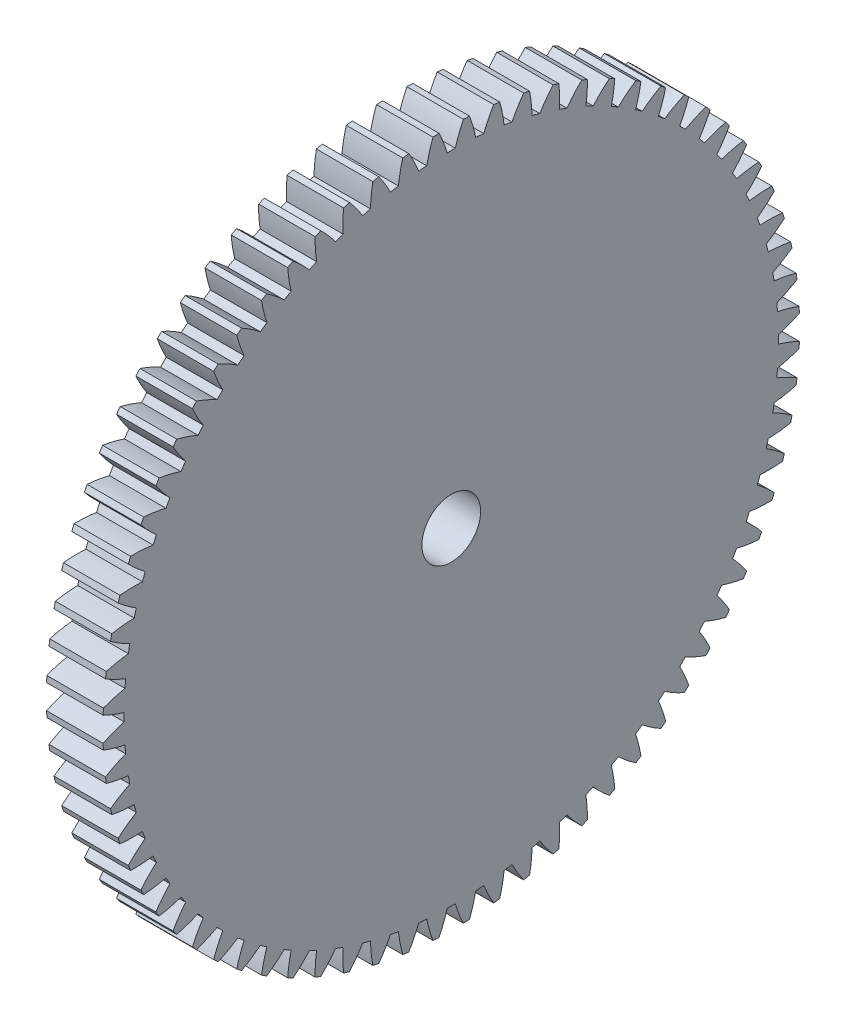
SolidWorks part; units mm, degrees
ref_plane "Front Plane" through (0, 0, 0) normal (0, 0, 1) x (1, 0, 0)
ref_plane "Top Plane" through (0, 0, 0) normal (0, 1, 0) x (1, 0, 0)
ref_plane "Right Plane" through (0, 0, 0) normal (1, 0, 0) x (0, 0, -1)
sketch "Sketch1" plane through (0, 0, 0) normal (0, 0, 1) x (1, 0, 0)
  line L0 (-10, 0) -> (60, 0) construction
  line L1 (0, 0) -> (0, 39.1583)
  line L2 (0, 0) -> (6.35, 0)
  line L3 (6.35, 0) -> (6.35, 39.1583)
  line L4 (6.35, 39.1583) -> (0, 39.1583)
  point P1 (0, 0)
  dimension "Diameter" = 78.3167
  dimension "Thickness" = 6.35
revolve "Revolve1" add sketch "Sketch1" angle 360 about L0
sketch "Sketch2" plane through (0, 0, 0) normal (-1, 0, 0) x (0, 0, 1)
  line L1 (0, 0) -> (0, 107) construction
  line L2 (0, 0) -> (-0.9058, 38.0892) construction
  line L3 (0, 0) -> (-3.3231, 76.1125) construction
  line L4 (-0.9058, 38.0892) -> (-1.6616, 38.0562) construction
  arc A0 (0.4536, 36.7764) -> (-0.4536, 36.7764) centre (0, 0) ccw
  arc A1 (1.3783, 39.1595) -> (-1.3783, 39.1595) centre (0, 0) ccw
  circle A2 centre (0, 0) radius 38.1 construction
  circle A3 centre (0, 0) radius 35.8023 construction
  arc A4 (-0.4536, 36.7764) -> (-1.3783, 39.1595) centre (-15.0738, 32.4744) ccw
  arc A5 (1.3783, 39.1595) -> (0.4536, 36.7764) centre (15.0738, 32.4744) ccw
  arc A6 (2.7534, 36.676) -> (2.0399, 39.1306) centre (-12.1861, 33.6646) ccw
  arc A7 (3.6571, 36.5969) -> (2.7534, 36.676) centre (0, 0) ccw
  arc A8 (4.786, 38.8903) -> (3.6571, 36.5969) centre (17.8467, 31.037) ccw
  arc A9 (4.786, 38.8903) -> (2.0399, 39.1306) centre (0, 0) ccw
  arc A10 (5.9395, 36.2965) -> (5.4426, 38.8039) centre (-9.2057, 34.5986) ccw
  arc A11 (6.8328, 36.1389) -> (5.9395, 36.2965) centre (0, 0) ccw
  arc A12 (8.1573, 38.3252) -> (6.8328, 36.1389) centre (20.4839, 29.3635) ccw
  arc A13 (8.1573, 38.3252) -> (5.4426, 38.8039) centre (0, 0) ccw
  arc A14 (9.0803, 35.6407) -> (8.8039, 38.1819) centre (-6.1552, 35.2692) ccw
  arc A15 (9.9566, 35.4059) -> (9.0803, 35.6407) centre (0, 0) ccw
  arc A16 (11.4665, 37.4684) -> (9.9566, 35.4059) centre (22.9651, 27.4665) ccw
  arc A17 (11.4665, 37.4684) -> (8.8039, 38.1819) centre (0, 0) ccw
  arc A18 (12.152, 34.7136) -> (12.0982, 37.2693) centre (-3.0578, 35.6715) ccw
  arc A19 (13.0045, 34.4034) -> (12.152, 34.7136) centre (0, 0) ccw
  arc A20 (14.6885, 36.3265) -> (13.0045, 34.4034) centre (25.2716, 25.3604) ccw
  arc A21 (14.6885, 36.3265) -> (12.0982, 37.2693) centre (0, 0) ccw
  arc A22 (15.1313, 33.5224) -> (15.3004, 36.073) centre (0.0628, 35.8022) ccw
  arc A23 (15.9535, 33.139) -> (15.1313, 33.5224) centre (0, 0) ccw
  arc A24 (17.7987, 34.9081) -> (15.9535, 33.139) centre (27.3857, 23.0613) ccw
  arc A25 (17.7987, 34.9081) -> (15.3004, 36.073) centre (0, 0) ccw
  arc A26 (17.9954, 32.0761) -> (18.3861, 34.6022) centre (3.1829, 35.6605) ccw
  arc A27 (18.781, 31.6225) -> (17.9954, 32.0761) centre (0, 0) ccw
  arc A28 (20.7734, 33.224) -> (18.781, 31.6225) centre (29.2915, 20.5867) ccw
  arc A29 (20.7734, 33.224) -> (18.3861, 34.6022) centre (0, 0) ccw
  arc A30 (20.7225, 30.3856) -> (21.3319, 32.8681) centre (6.2788, 35.2474) ccw
  arc A31 (21.4656, 29.8653) -> (20.7225, 30.3856) centre (0, 0) ccw
  arc A32 (23.59, 31.287) -> (21.4656, 29.8653) centre (30.9743, 17.9555) ccw
  arc A33 (23.59, 31.287) -> (21.3319, 32.8681) centre (0, 0) ccw
  arc A34 (23.292, 28.4639) -> (24.1154, 30.8838) centre (9.3269, 34.5661) ccw
  arc A35 (23.9869, 27.8808) -> (23.292, 28.4639) centre (0, 0) ccw
  arc A36 (26.227, 29.112) -> (23.9869, 27.8808) centre (32.4213, 15.1876) ccw
  arc A37 (26.227, 29.112) -> (24.1154, 30.8838) centre (0, 0) ccw
  arc A38 (25.6841, 26.3256) -> (26.7154, 28.6645) centre (12.3041, 33.6216) ccw
  arc A39 (26.3256, 25.6841) -> (25.6841, 26.3256) centre (0, 0) ccw
  arc A40 (28.6645, 26.7154) -> (26.3256, 25.6841) centre (33.6216, 12.3041) ccw
  arc A41 (28.6645, 26.7154) -> (26.7154, 28.6645) centre (0, 0) ccw
  arc A42 (27.8808, 23.9869) -> (29.112, 26.227) centre (15.1876, 32.4213) ccw
  arc A43 (28.4639, 23.292) -> (27.8808, 23.9869) centre (0, 0) ccw
  arc A44 (30.8838, 24.1154) -> (28.4639, 23.292) centre (34.5661, 9.3269) ccw
  arc A45 (30.8838, 24.1154) -> (29.112, 26.227) centre (0, 0) ccw
  arc A46 (29.8653, 21.4656) -> (31.287, 23.59) centre (17.9555, 30.9743) ccw
  arc A47 (30.3856, 20.7225) -> (29.8653, 21.4656) centre (0, 0) ccw
  arc A48 (32.8681, 21.3319) -> (30.3856, 20.7225) centre (35.2474, 6.2788) ccw
  arc A49 (32.8681, 21.3319) -> (31.287, 23.59) centre (0, 0) ccw
  arc A50 (31.6225, 18.781) -> (33.224, 20.7734) centre (20.5867, 29.2915) ccw
  arc A51 (32.0761, 17.9954) -> (31.6225, 18.781) centre (0, 0) ccw
  arc A52 (34.6022, 18.3861) -> (32.0761, 17.9954) centre (35.6605, 3.1829) ccw
  arc A53 (34.6022, 18.3861) -> (33.224, 20.7734) centre (0, 0) ccw
  arc A54 (33.139, 15.9535) -> (34.9081, 17.7987) centre (23.0613, 27.3857) ccw
  arc A55 (33.5224, 15.1313) -> (33.139, 15.9535) centre (0, 0) ccw
  arc A56 (36.073, 15.3004) -> (33.5224, 15.1313) centre (35.8022, 0.0628) ccw
  arc A57 (36.073, 15.3004) -> (34.9081, 17.7987) centre (0, 0) ccw
  arc A58 (34.4034, 13.0045) -> (36.3265, 14.6885) centre (25.3604, 25.2716) ccw
  arc A59 (34.7136, 12.152) -> (34.4034, 13.0045) centre (0, 0) ccw
  arc A60 (37.2693, 12.0982) -> (34.7136, 12.152) centre (35.6715, -3.0578) ccw
  arc A61 (37.2693, 12.0982) -> (36.3265, 14.6885) centre (0, 0) ccw
  arc A62 (35.4059, 9.9566) -> (37.4684, 11.4665) centre (27.4665, 22.9651) ccw
  arc A63 (35.6407, 9.0803) -> (35.4059, 9.9566) centre (0, 0) ccw
  arc A64 (38.1819, 8.8039) -> (35.6407, 9.0803) centre (35.2692, -6.1552) ccw
  arc A65 (38.1819, 8.8039) -> (37.4684, 11.4665) centre (0, 0) ccw
  arc A66 (36.1389, 6.8328) -> (38.3252, 8.1573) centre (29.3635, 20.4839) ccw
  arc A67 (36.2965, 5.9395) -> (36.1389, 6.8328) centre (0, 0) ccw
  arc A68 (38.8039, 5.4426) -> (36.2965, 5.9395) centre (34.5986, -9.2057) ccw
  arc A69 (38.8039, 5.4426) -> (38.3252, 8.1573) centre (0, 0) ccw
  arc A70 (36.5969, 3.6571) -> (38.8903, 4.786) centre (31.037, 17.8467) ccw
  arc A71 (36.676, 2.7534) -> (36.5969, 3.6571) centre (0, 0) ccw
  arc A72 (39.1306, 2.0399) -> (36.676, 2.7534) centre (33.6646, -12.1861) ccw
  arc A73 (39.1306, 2.0399) -> (38.8903, 4.786) centre (0, 0) ccw
  arc A74 (36.7764, 0.4536) -> (39.1595, 1.3783) centre (32.4744, 15.0738) ccw
  arc A75 (36.7764, -0.4536) -> (36.7764, 0.4536) centre (0, 0) ccw
  arc A76 (39.1595, -1.3783) -> (36.7764, -0.4536) centre (32.4744, -15.0738) ccw
  arc A77 (39.1595, -1.3783) -> (39.1595, 1.3783) centre (0, 0) ccw
  arc A78 (36.676, -2.7534) -> (39.1306, -2.0399) centre (33.6646, 12.1861) ccw
  arc A79 (36.5969, -3.6571) -> (36.676, -2.7534) centre (0, 0) ccw
  arc A80 (38.8903, -4.786) -> (36.5969, -3.6571) centre (31.037, -17.8467) ccw
  arc A81 (38.8903, -4.786) -> (39.1306, -2.0399) centre (0, 0) ccw
  arc A82 (36.2965, -5.9395) -> (38.8039, -5.4426) centre (34.5986, 9.2057) ccw
  arc A83 (36.1389, -6.8328) -> (36.2965, -5.9395) centre (0, 0) ccw
  arc A84 (38.3252, -8.1573) -> (36.1389, -6.8328) centre (29.3635, -20.4839) ccw
  arc A85 (38.3252, -8.1573) -> (38.8039, -5.4426) centre (0, 0) ccw
  arc A86 (35.6407, -9.0803) -> (38.1819, -8.8039) centre (35.2692, 6.1552) ccw
  arc A87 (35.4059, -9.9566) -> (35.6407, -9.0803) centre (0, 0) ccw
  arc A88 (37.4684, -11.4665) -> (35.4059, -9.9566) centre (27.4665, -22.9651) ccw
  arc A89 (37.4684, -11.4665) -> (38.1819, -8.8039) centre (0, 0) ccw
  arc A90 (34.7136, -12.152) -> (37.2693, -12.0982) centre (35.6715, 3.0578) ccw
  arc A91 (34.4034, -13.0045) -> (34.7136, -12.152) centre (0, 0) ccw
  arc A92 (36.3265, -14.6885) -> (34.4034, -13.0045) centre (25.3604, -25.2716) ccw
  arc A93 (36.3265, -14.6885) -> (37.2693, -12.0982) centre (0, 0) ccw
  arc A94 (33.5224, -15.1313) -> (36.073, -15.3004) centre (35.8022, -0.0628) ccw
  arc A95 (33.139, -15.9535) -> (33.5224, -15.1313) centre (0, 0) ccw
  arc A96 (34.9081, -17.7987) -> (33.139, -15.9535) centre (23.0613, -27.3857) ccw
  arc A97 (34.9081, -17.7987) -> (36.073, -15.3004) centre (0, 0) ccw
  arc A98 (32.0761, -17.9954) -> (34.6022, -18.3861) centre (35.6605, -3.1829) ccw
  arc A99 (31.6225, -18.781) -> (32.0761, -17.9954) centre (0, 0) ccw
  arc A100 (33.224, -20.7734) -> (31.6225, -18.781) centre (20.5867, -29.2915) ccw
  arc A101 (33.224, -20.7734) -> (34.6022, -18.3861) centre (0, 0) ccw
  arc A102 (30.3856, -20.7225) -> (32.8681, -21.3319) centre (35.2474, -6.2788) ccw
  arc A103 (29.8653, -21.4656) -> (30.3856, -20.7225) centre (0, 0) ccw
  arc A104 (31.287, -23.59) -> (29.8653, -21.4656) centre (17.9555, -30.9743) ccw
  arc A105 (31.287, -23.59) -> (32.8681, -21.3319) centre (0, 0) ccw
  arc A106 (28.4639, -23.292) -> (30.8838, -24.1154) centre (34.5661, -9.3269) ccw
  arc A107 (27.8808, -23.9869) -> (28.4639, -23.292) centre (0, 0) ccw
  arc A108 (29.112, -26.227) -> (27.8808, -23.9869) centre (15.1876, -32.4213) ccw
  arc A109 (29.112, -26.227) -> (30.8838, -24.1154) centre (0, 0) ccw
  arc A110 (26.3256, -25.6841) -> (28.6645, -26.7154) centre (33.6216, -12.3041) ccw
  arc A111 (25.6841, -26.3256) -> (26.3256, -25.6841) centre (0, 0) ccw
  arc A112 (26.7154, -28.6645) -> (25.6841, -26.3256) centre (12.3041, -33.6216) ccw
  arc A113 (26.7154, -28.6645) -> (28.6645, -26.7154) centre (0, 0) ccw
  arc A114 (23.9869, -27.8808) -> (26.227, -29.112) centre (32.4213, -15.1876) ccw
  arc A115 (23.292, -28.4639) -> (23.9869, -27.8808) centre (0, 0) ccw
  arc A116 (24.1154, -30.8838) -> (23.292, -28.4639) centre (9.3269, -34.5661) ccw
  arc A117 (24.1154, -30.8838) -> (26.227, -29.112) centre (0, 0) ccw
  arc A118 (21.4656, -29.8653) -> (23.59, -31.287) centre (30.9743, -17.9555) ccw
  arc A119 (20.7225, -30.3856) -> (21.4656, -29.8653) centre (0, 0) ccw
  arc A120 (21.3319, -32.8681) -> (20.7225, -30.3856) centre (6.2788, -35.2474) ccw
  arc A121 (21.3319, -32.8681) -> (23.59, -31.287) centre (0, 0) ccw
  arc A122 (18.781, -31.6225) -> (20.7734, -33.224) centre (29.2915, -20.5867) ccw
  arc A123 (17.9954, -32.0761) -> (18.781, -31.6225) centre (0, 0) ccw
  arc A124 (18.3861, -34.6022) -> (17.9954, -32.0761) centre (3.1829, -35.6605) ccw
  arc A125 (18.3861, -34.6022) -> (20.7734, -33.224) centre (0, 0) ccw
  arc A126 (15.9535, -33.139) -> (17.7987, -34.9081) centre (27.3857, -23.0613) ccw
  arc A127 (15.1313, -33.5224) -> (15.9535, -33.139) centre (0, 0) ccw
  arc A128 (15.3004, -36.073) -> (15.1313, -33.5224) centre (0.0628, -35.8022) ccw
  arc A129 (15.3004, -36.073) -> (17.7987, -34.9081) centre (0, 0) ccw
  arc A130 (13.0045, -34.4034) -> (14.6885, -36.3265) centre (25.2716, -25.3604) ccw
  arc A131 (12.152, -34.7136) -> (13.0045, -34.4034) centre (0, 0) ccw
  arc A132 (12.0982, -37.2693) -> (12.152, -34.7136) centre (-3.0578, -35.6715) ccw
  arc A133 (12.0982, -37.2693) -> (14.6885, -36.3265) centre (0, 0) ccw
  arc A134 (9.9566, -35.4059) -> (11.4665, -37.4684) centre (22.9651, -27.4665) ccw
  arc A135 (9.0803, -35.6407) -> (9.9566, -35.4059) centre (0, 0) ccw
  arc A136 (8.8039, -38.1819) -> (9.0803, -35.6407) centre (-6.1552, -35.2692) ccw
  arc A137 (8.8039, -38.1819) -> (11.4665, -37.4684) centre (0, 0) ccw
  arc A138 (6.8328, -36.1389) -> (8.1573, -38.3252) centre (20.4839, -29.3635) ccw
  arc A139 (5.9395, -36.2965) -> (6.8328, -36.1389) centre (0, 0) ccw
  arc A140 (5.4426, -38.8039) -> (5.9395, -36.2965) centre (-9.2057, -34.5986) ccw
  arc A141 (5.4426, -38.8039) -> (8.1573, -38.3252) centre (0, 0) ccw
  arc A142 (3.6571, -36.5969) -> (4.786, -38.8903) centre (17.8467, -31.037) ccw
  arc A143 (2.7534, -36.676) -> (3.6571, -36.5969) centre (0, 0) ccw
  arc A144 (2.0399, -39.1306) -> (2.7534, -36.676) centre (-12.1861, -33.6646) ccw
  arc A145 (2.0399, -39.1306) -> (4.786, -38.8903) centre (0, 0) ccw
  arc A146 (0.4536, -36.7764) -> (1.3783, -39.1595) centre (15.0738, -32.4744) ccw
  arc A147 (-0.4536, -36.7764) -> (0.4536, -36.7764) centre (0, 0) ccw
  arc A148 (-1.3783, -39.1595) -> (-0.4536, -36.7764) centre (-15.0738, -32.4744) ccw
  arc A149 (-1.3783, -39.1595) -> (1.3783, -39.1595) centre (0, 0) ccw
  arc A150 (-2.7534, -36.676) -> (-2.0399, -39.1306) centre (12.1861, -33.6646) ccw
  arc A151 (-3.6571, -36.5969) -> (-2.7534, -36.676) centre (0, 0) ccw
  arc A152 (-4.786, -38.8903) -> (-3.6571, -36.5969) centre (-17.8467, -31.037) ccw
  arc A153 (-4.786, -38.8903) -> (-2.0399, -39.1306) centre (0, 0) ccw
  arc A154 (-5.9395, -36.2965) -> (-5.4426, -38.8039) centre (9.2057, -34.5986) ccw
  arc A155 (-6.8328, -36.1389) -> (-5.9395, -36.2965) centre (0, 0) ccw
  arc A156 (-8.1573, -38.3252) -> (-6.8328, -36.1389) centre (-20.4839, -29.3635) ccw
  arc A157 (-8.1573, -38.3252) -> (-5.4426, -38.8039) centre (0, 0) ccw
  arc A158 (-9.0803, -35.6407) -> (-8.8039, -38.1819) centre (6.1552, -35.2692) ccw
  arc A159 (-9.9566, -35.4059) -> (-9.0803, -35.6407) centre (0, 0) ccw
  arc A160 (-11.4665, -37.4684) -> (-9.9566, -35.4059) centre (-22.9651, -27.4665) ccw
  arc A161 (-11.4665, -37.4684) -> (-8.8039, -38.1819) centre (0, 0) ccw
  arc A162 (-12.152, -34.7136) -> (-12.0982, -37.2693) centre (3.0578, -35.6715) ccw
  arc A163 (-13.0045, -34.4034) -> (-12.152, -34.7136) centre (0, 0) ccw
  arc A164 (-14.6885, -36.3265) -> (-13.0045, -34.4034) centre (-25.2716, -25.3604) ccw
  arc A165 (-14.6885, -36.3265) -> (-12.0982, -37.2693) centre (0, 0) ccw
  arc A166 (-15.1313, -33.5224) -> (-15.3004, -36.073) centre (-0.0628, -35.8022) ccw
  arc A167 (-15.9535, -33.139) -> (-15.1313, -33.5224) centre (0, 0) ccw
  arc A168 (-17.7987, -34.9081) -> (-15.9535, -33.139) centre (-27.3857, -23.0613) ccw
  arc A169 (-17.7987, -34.9081) -> (-15.3004, -36.073) centre (0, 0) ccw
  arc A170 (-17.9954, -32.0761) -> (-18.3861, -34.6022) centre (-3.1829, -35.6605) ccw
  arc A171 (-18.781, -31.6225) -> (-17.9954, -32.0761) centre (0, 0) ccw
  arc A172 (-20.7734, -33.224) -> (-18.781, -31.6225) centre (-29.2915, -20.5867) ccw
  arc A173 (-20.7734, -33.224) -> (-18.3861, -34.6022) centre (0, 0) ccw
  arc A174 (-20.7225, -30.3856) -> (-21.3319, -32.8681) centre (-6.2788, -35.2474) ccw
  arc A175 (-21.4656, -29.8653) -> (-20.7225, -30.3856) centre (0, 0) ccw
  arc A176 (-23.59, -31.287) -> (-21.4656, -29.8653) centre (-30.9743, -17.9555) ccw
  arc A177 (-23.59, -31.287) -> (-21.3319, -32.8681) centre (0, 0) ccw
  arc A178 (-23.292, -28.4639) -> (-24.1154, -30.8838) centre (-9.3269, -34.5661) ccw
  arc A179 (-23.9869, -27.8808) -> (-23.292, -28.4639) centre (0, 0) ccw
  arc A180 (-26.227, -29.112) -> (-23.9869, -27.8808) centre (-32.4213, -15.1876) ccw
  arc A181 (-26.227, -29.112) -> (-24.1154, -30.8838) centre (0, 0) ccw
  arc A182 (-25.6841, -26.3256) -> (-26.7154, -28.6645) centre (-12.3041, -33.6216) ccw
  arc A183 (-26.3256, -25.6841) -> (-25.6841, -26.3256) centre (0, 0) ccw
  arc A184 (-28.6645, -26.7154) -> (-26.3256, -25.6841) centre (-33.6216, -12.3041) ccw
  arc A185 (-28.6645, -26.7154) -> (-26.7154, -28.6645) centre (0, 0) ccw
  arc A186 (-27.8808, -23.9869) -> (-29.112, -26.227) centre (-15.1876, -32.4213) ccw
  arc A187 (-28.4639, -23.292) -> (-27.8808, -23.9869) centre (0, 0) ccw
  arc A188 (-30.8838, -24.1154) -> (-28.4639, -23.292) centre (-34.5661, -9.3269) ccw
  arc A189 (-30.8838, -24.1154) -> (-29.112, -26.227) centre (0, 0) ccw
  arc A190 (-29.8653, -21.4656) -> (-31.287, -23.59) centre (-17.9555, -30.9743) ccw
  arc A191 (-30.3856, -20.7225) -> (-29.8653, -21.4656) centre (0, 0) ccw
  arc A192 (-32.8681, -21.3319) -> (-30.3856, -20.7225) centre (-35.2474, -6.2788) ccw
  arc A193 (-32.8681, -21.3319) -> (-31.287, -23.59) centre (0, 0) ccw
  arc A194 (-31.6225, -18.781) -> (-33.224, -20.7734) centre (-20.5867, -29.2915) ccw
  arc A195 (-32.0761, -17.9954) -> (-31.6225, -18.781) centre (0, 0) ccw
  arc A196 (-34.6022, -18.3861) -> (-32.0761, -17.9954) centre (-35.6605, -3.1829) ccw
  arc A197 (-34.6022, -18.3861) -> (-33.224, -20.7734) centre (0, 0) ccw
  arc A198 (-33.139, -15.9535) -> (-34.9081, -17.7987) centre (-23.0613, -27.3857) ccw
  arc A199 (-33.5224, -15.1313) -> (-33.139, -15.9535) centre (0, 0) ccw
  arc A200 (-36.073, -15.3004) -> (-33.5224, -15.1313) centre (-35.8022, -0.0628) ccw
  arc A201 (-36.073, -15.3004) -> (-34.9081, -17.7987) centre (0, 0) ccw
  arc A202 (-34.4034, -13.0045) -> (-36.3265, -14.6885) centre (-25.3604, -25.2716) ccw
  arc A203 (-34.7136, -12.152) -> (-34.4034, -13.0045) centre (0, 0) ccw
  arc A204 (-37.2693, -12.0982) -> (-34.7136, -12.152) centre (-35.6715, 3.0578) ccw
  arc A205 (-37.2693, -12.0982) -> (-36.3265, -14.6885) centre (0, 0) ccw
  arc A206 (-35.4059, -9.9566) -> (-37.4684, -11.4665) centre (-27.4665, -22.9651) ccw
  arc A207 (-35.6407, -9.0803) -> (-35.4059, -9.9566) centre (0, 0) ccw
  arc A208 (-38.1819, -8.8039) -> (-35.6407, -9.0803) centre (-35.2692, 6.1552) ccw
  arc A209 (-38.1819, -8.8039) -> (-37.4684, -11.4665) centre (0, 0) ccw
  arc A210 (-36.1389, -6.8328) -> (-38.3252, -8.1573) centre (-29.3635, -20.4839) ccw
  arc A211 (-36.2965, -5.9395) -> (-36.1389, -6.8328) centre (0, 0) ccw
  arc A212 (-38.8039, -5.4426) -> (-36.2965, -5.9395) centre (-34.5986, 9.2057) ccw
  arc A213 (-38.8039, -5.4426) -> (-38.3252, -8.1573) centre (0, 0) ccw
  arc A214 (-36.5969, -3.6571) -> (-38.8903, -4.786) centre (-31.037, -17.8467) ccw
  arc A215 (-36.676, -2.7534) -> (-36.5969, -3.6571) centre (0, 0) ccw
  arc A216 (-39.1306, -2.0399) -> (-36.676, -2.7534) centre (-33.6646, 12.1861) ccw
  arc A217 (-39.1306, -2.0399) -> (-38.8903, -4.786) centre (0, 0) ccw
  arc A218 (-36.7764, -0.4536) -> (-39.1595, -1.3783) centre (-32.4744, -15.0738) ccw
  arc A219 (-36.7764, 0.4536) -> (-36.7764, -0.4536) centre (0, 0) ccw
  arc A220 (-39.1595, 1.3783) -> (-36.7764, 0.4536) centre (-32.4744, 15.0738) ccw
  arc A221 (-39.1595, 1.3783) -> (-39.1595, -1.3783) centre (0, 0) ccw
  arc A222 (-36.676, 2.7534) -> (-39.1306, 2.0399) centre (-33.6646, -12.1861) ccw
  arc A223 (-36.5969, 3.6571) -> (-36.676, 2.7534) centre (0, 0) ccw
  arc A224 (-38.8903, 4.786) -> (-36.5969, 3.6571) centre (-31.037, 17.8467) ccw
  arc A225 (-38.8903, 4.786) -> (-39.1306, 2.0399) centre (0, 0) ccw
  arc A226 (-36.2965, 5.9395) -> (-38.8039, 5.4426) centre (-34.5986, -9.2057) ccw
  arc A227 (-36.1389, 6.8328) -> (-36.2965, 5.9395) centre (0, 0) ccw
  arc A228 (-38.3252, 8.1573) -> (-36.1389, 6.8328) centre (-29.3635, 20.4839) ccw
  arc A229 (-38.3252, 8.1573) -> (-38.8039, 5.4426) centre (0, 0) ccw
  arc A230 (-35.6407, 9.0803) -> (-38.1819, 8.8039) centre (-35.2692, -6.1552) ccw
  arc A231 (-35.4059, 9.9566) -> (-35.6407, 9.0803) centre (0, 0) ccw
  arc A232 (-37.4684, 11.4665) -> (-35.4059, 9.9566) centre (-27.4665, 22.9651) ccw
  arc A233 (-37.4684, 11.4665) -> (-38.1819, 8.8039) centre (0, 0) ccw
  arc A234 (-34.7136, 12.152) -> (-37.2693, 12.0982) centre (-35.6715, -3.0578) ccw
  arc A235 (-34.4034, 13.0045) -> (-34.7136, 12.152) centre (0, 0) ccw
  arc A236 (-36.3265, 14.6885) -> (-34.4034, 13.0045) centre (-25.3604, 25.2716) ccw
  arc A237 (-36.3265, 14.6885) -> (-37.2693, 12.0982) centre (0, 0) ccw
  arc A238 (-33.5224, 15.1313) -> (-36.073, 15.3004) centre (-35.8022, 0.0628) ccw
  arc A239 (-33.139, 15.9535) -> (-33.5224, 15.1313) centre (0, 0) ccw
  arc A240 (-34.9081, 17.7987) -> (-33.139, 15.9535) centre (-23.0613, 27.3857) ccw
  arc A241 (-34.9081, 17.7987) -> (-36.073, 15.3004) centre (0, 0) ccw
  arc A242 (-32.0761, 17.9954) -> (-34.6022, 18.3861) centre (-35.6605, 3.1829) ccw
  arc A243 (-31.6225, 18.781) -> (-32.0761, 17.9954) centre (0, 0) ccw
  arc A244 (-33.224, 20.7734) -> (-31.6225, 18.781) centre (-20.5867, 29.2915) ccw
  arc A245 (-33.224, 20.7734) -> (-34.6022, 18.3861) centre (0, 0) ccw
  arc A246 (-30.3856, 20.7225) -> (-32.8681, 21.3319) centre (-35.2474, 6.2788) ccw
  arc A247 (-29.8653, 21.4656) -> (-30.3856, 20.7225) centre (0, 0) ccw
  arc A248 (-31.287, 23.59) -> (-29.8653, 21.4656) centre (-17.9555, 30.9743) ccw
  arc A249 (-31.287, 23.59) -> (-32.8681, 21.3319) centre (0, 0) ccw
  arc A250 (-28.4639, 23.292) -> (-30.8838, 24.1154) centre (-34.5661, 9.3269) ccw
  arc A251 (-27.8808, 23.9869) -> (-28.4639, 23.292) centre (0, 0) ccw
  arc A252 (-29.112, 26.227) -> (-27.8808, 23.9869) centre (-15.1876, 32.4213) ccw
  arc A253 (-29.112, 26.227) -> (-30.8838, 24.1154) centre (0, 0) ccw
  arc A254 (-26.3256, 25.6841) -> (-28.6645, 26.7154) centre (-33.6216, 12.3041) ccw
  arc A255 (-25.6841, 26.3256) -> (-26.3256, 25.6841) centre (0, 0) ccw
  arc A256 (-26.7154, 28.6645) -> (-25.6841, 26.3256) centre (-12.3041, 33.6216) ccw
  arc A257 (-26.7154, 28.6645) -> (-28.6645, 26.7154) centre (0, 0) ccw
  arc A258 (-23.9869, 27.8808) -> (-26.227, 29.112) centre (-32.4213, 15.1876) ccw
  arc A259 (-23.292, 28.4639) -> (-23.9869, 27.8808) centre (0, 0) ccw
  arc A260 (-24.1154, 30.8838) -> (-23.292, 28.4639) centre (-9.3269, 34.5661) ccw
  arc A261 (-24.1154, 30.8838) -> (-26.227, 29.112) centre (0, 0) ccw
  arc A262 (-21.4656, 29.8653) -> (-23.59, 31.287) centre (-30.9743, 17.9555) ccw
  arc A263 (-20.7225, 30.3856) -> (-21.4656, 29.8653) centre (0, 0) ccw
  arc A264 (-21.3319, 32.8681) -> (-20.7225, 30.3856) centre (-6.2788, 35.2474) ccw
  arc A265 (-21.3319, 32.8681) -> (-23.59, 31.287) centre (0, 0) ccw
  arc A266 (-18.781, 31.6225) -> (-20.7734, 33.224) centre (-29.2915, 20.5867) ccw
  arc A267 (-17.9954, 32.0761) -> (-18.781, 31.6225) centre (0, 0) ccw
  arc A268 (-18.3861, 34.6022) -> (-17.9954, 32.0761) centre (-3.1829, 35.6605) ccw
  arc A269 (-18.3861, 34.6022) -> (-20.7734, 33.224) centre (0, 0) ccw
  arc A270 (-15.9535, 33.139) -> (-17.7987, 34.9081) centre (-27.3857, 23.0613) ccw
  arc A271 (-15.1313, 33.5224) -> (-15.9535, 33.139) centre (0, 0) ccw
  arc A272 (-15.3004, 36.073) -> (-15.1313, 33.5224) centre (-0.0628, 35.8022) ccw
  arc A273 (-15.3004, 36.073) -> (-17.7987, 34.9081) centre (0, 0) ccw
  arc A274 (-13.0045, 34.4034) -> (-14.6885, 36.3265) centre (-25.2716, 25.3604) ccw
  arc A275 (-12.152, 34.7136) -> (-13.0045, 34.4034) centre (0, 0) ccw
  arc A276 (-12.0982, 37.2693) -> (-12.152, 34.7136) centre (3.0578, 35.6715) ccw
  arc A277 (-12.0982, 37.2693) -> (-14.6885, 36.3265) centre (0, 0) ccw
  arc A278 (-9.9566, 35.4059) -> (-11.4665, 37.4684) centre (-22.9651, 27.4665) ccw
  arc A279 (-9.0803, 35.6407) -> (-9.9566, 35.4059) centre (0, 0) ccw
  arc A280 (-8.8039, 38.1819) -> (-9.0803, 35.6407) centre (6.1552, 35.2692) ccw
  arc A281 (-8.8039, 38.1819) -> (-11.4665, 37.4684) centre (0, 0) ccw
  arc A282 (-6.8328, 36.1389) -> (-8.1573, 38.3252) centre (-20.4839, 29.3635) ccw
  arc A283 (-5.9395, 36.2965) -> (-6.8328, 36.1389) centre (0, 0) ccw
  arc A284 (-5.4426, 38.8039) -> (-5.9395, 36.2965) centre (9.2057, 34.5986) ccw
  arc A285 (-5.4426, 38.8039) -> (-8.1573, 38.3252) centre (0, 0) ccw
  arc A286 (-3.6571, 36.5969) -> (-4.786, 38.8903) centre (-17.8467, 31.037) ccw
  arc A287 (-2.7534, 36.676) -> (-3.6571, 36.5969) centre (0, 0) ccw
  arc A288 (-2.0399, 39.1306) -> (-2.7534, 36.676) centre (12.1861, 33.6646) ccw
  arc A289 (-2.0399, 39.1306) -> (-4.786, 38.8903) centre (0, 0) ccw
  point P444 (0, 0)
  dimension "Root_dia" = 73.5584
  dimension "Overcut_dia" = 78.3675
  dimension "Pitch_dia" = 76.2
  dimension "Base_dia" = 71.6046
  dimension "Flank_rad" = 15.24
  dimension "Half_ang" = 2.5
  dimension "Half_CT" = 0.7565
extrude "Cut-Extrude1" cut sketch "Sketch2" against normal through all
sketch "Sketch5" plane through (0, 0, 0) normal (-1, 0, 0) x (0, 0, 1)
  circle A0 centre (0, 0) radius 3.302
  dimension "D1" = 6.604
extrude "Cut-Extrude3" cut sketch "Sketch5" against normal through all contours A0
